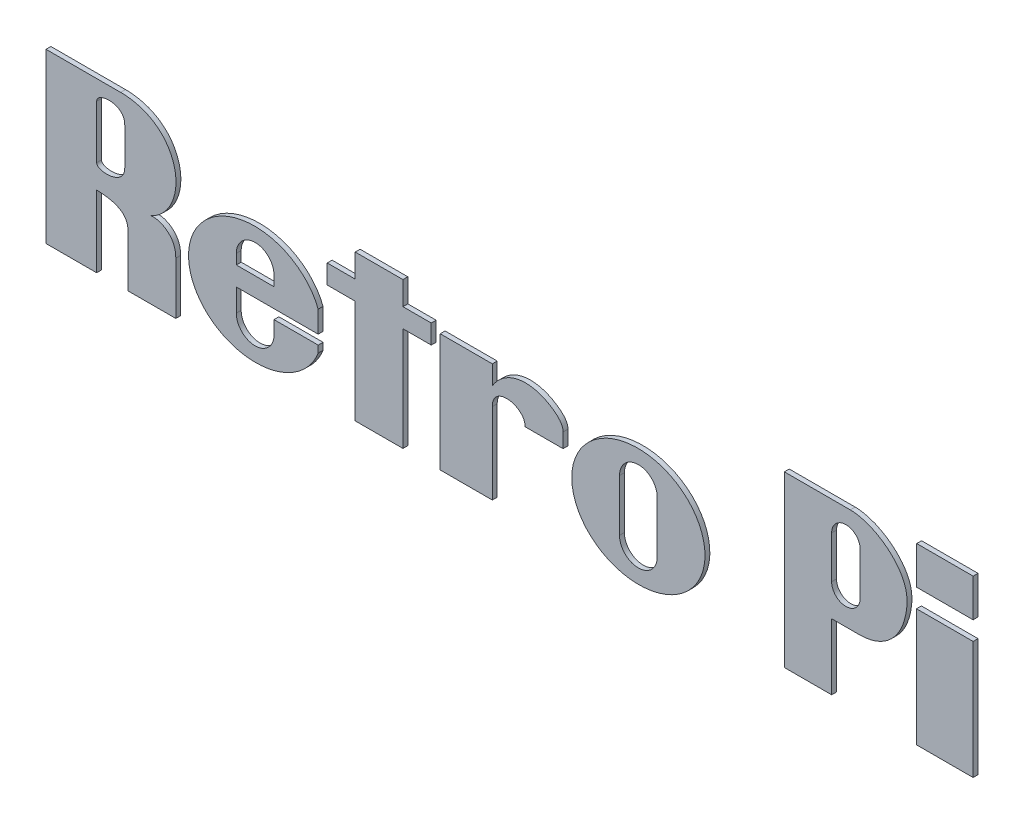
SolidWorks part; units mm, degrees
ref_plane "Front Plane" through (0, 0, 0) normal (0, 0, 1) x (1, 0, 0)
ref_plane "Top Plane" through (0, 0, 0) normal (0, 1, 0) x (1, 0, 0)
ref_plane "Right Plane" through (0, 0, 0) normal (1, 0, 0) x (0, 0, -1)
sketch "Sketch1" plane through (0, 0, 0) normal (0, 0, 1) x (1, 0, 0)
  line L0 (7.695, 27.3237) -> (140.3617, 27.3237) construction
  line L1 (-30.2633, -2.8229) -> (-30.2633, -4.6928)
  line L2 (-30.2633, -4.6928) -> (-31.5821, -4.6928)
  line L3 (-31.5821, -4.6928) -> (-31.5821, -0.3107)
  line L4 (-31.5821, -0.3107) -> (-29.6366, -0.3107)
  line L5 (-30.2633, -2.2096) -> (-30.2633, -0.8264)
  line L6 (-28.2011, -3.3328) -> (-28.2011, -4.6928)
  line L7 (-28.2011, -4.6928) -> (-29.4478, -4.6928)
  line L8 (-29.4478, -4.6928) -> (-29.4478, -3.3328)
  line L9 (-26.134, -2.4358) -> (-26.134, -3.7851) construction
  line L10 (-25.6426, -2.4358) -> (-25.6426, -2.6977)
  line L11 (-26.6254, -2.4358) -> (-26.6254, -2.6977)
  line L12 (-23.5277, -1.9664) -> (-23.5277, -4.6667)
  line L13 (-24.2562, -1.4682) -> (-23.5277, -1.4682)
  line L14 (-24.2562, -1.4682) -> (-24.2562, -1.9664)
  line L15 (-24.2562, -1.9664) -> (-23.5277, -1.9664)
  line L16 (-21.5475, -1.4682) -> (-21.5475, -1.9664)
  line L17 (-23.5277, -0.8569) -> (-22.2843, -0.8569)
  line L18 (-23.5277, -0.8569) -> (-23.5277, -1.4682)
  line L19 (-23.5277, -4.6667) -> (-22.2843, -4.6667)
  line L20 (-22.2843, -0.8569) -> (-22.2843, -1.4682)
  line L21 (-22.2843, -1.4682) -> (-21.5475, -1.4682)
  line L22 (-22.2843, -1.9664) -> (-22.2843, -4.6667)
  line L23 (-22.2843, -1.9664) -> (-21.5475, -1.9664)
  line L24 (-29.5308, -0.988) -> (-29.5308, -1.9664)
  line L25 (-21.313, -1.5938) -> (-19.9566, -1.5938)
  line L26 (-21.313, -1.5938) -> (-21.313, -4.6667)
  line L27 (-21.313, -4.6667) -> (-19.9566, -4.6667)
  line L28 (-19.9566, -1.5938) -> (-19.9566, -2.0894)
  line L29 (-12.3495, -0.2259) -> (-10.6322, -0.2259)
  line L30 (-12.3495, -0.2259) -> (-12.3495, -4.6407)
  line L31 (-12.3495, -4.6407) -> (-11.1172, -4.6407)
  line L32 (-11.1172, -4.6407) -> (-11.1172, -2.9238)
  line L33 (-8.9022, -0.1203) -> (-7.4323, -0.1203)
  line L34 (-8.9022, -0.1203) -> (-8.9022, -1.1066)
  line L35 (-8.9022, -1.1066) -> (-7.4323, -1.1066)
  line L36 (-7.4323, -0.1203) -> (-7.4323, -1.1066)
  line L37 (-8.907, -1.5938) -> (-7.4323, -1.5938)
  line L38 (-8.907, -1.5938) -> (-8.907, -4.664)
  line L39 (-8.907, -4.664) -> (-7.4323, -4.664)
  line L40 (-7.4323, -1.5938) -> (-7.4323, -4.664)
  line L41 (-24.4919, -2.6294) -> (-24.4919, -3.1934)
  line L42 (-17.6786, -2.3552) -> (-17.6786, -2.5863) construction
  line L43 (-24.4919, -3.4389) -> (-25.6426, -3.4389)
  line L44 (-24.4919, -3.1934) -> (-26.6254, -3.1934)
  line L45 (-19.1018, -2.5863) -> (-18.1131, -2.5863)
  line L46 (-18.1131, -2.5863) -> (-18.1131, -2.2096)
  line L47 (-19.9566, -2.5595) -> (-19.9566, -4.6667)
  line L48 (-16.1521, -2.4557) -> (-16.1521, -3.805) construction
  line L49 (-15.6608, -2.4557) -> (-15.6608, -3.805)
  line L50 (-16.6435, -2.4557) -> (-16.6435, -3.805)
  line L51 (-26.6254, -2.6977) -> (-25.6426, -2.6977)
  line L52 (-24.4919, -3.4389) -> (-24.4919, -3.6194)
  line L53 (-25.6426, -3.4389) -> (-25.6426, -3.7851)
  line L54 (-26.6254, -3.1934) -> (-26.6254, -3.7851)
  line L55 (-10.7458, -0.988) -> (-10.7458, -2.0894) construction
  line L56 (-10.3735, -0.988) -> (-10.3735, -2.0894)
  line L57 (-11.118, -0.988) -> (-11.118, -2.0894)
  line L58 (-11.1172, -2.9238) -> (-10.3913, -2.9238)
  arc A0 (-15.6608, -2.4557) -> (-16.6435, -2.4557) centre (-16.1521, -2.4557) ccw
  arc A1 (-16.6435, -3.805) -> (-15.6608, -3.805) centre (-16.1521, -3.805) ccw
  arc A2 (-25.6426, -2.4358) -> (-26.6254, -2.4358) centre (-26.134, -2.4358) ccw
  arc A3 (-26.6254, -3.7851) -> (-25.6426, -3.7851) centre (-26.134, -3.7851) ccw
  arc A4 (-10.3735, -0.988) -> (-11.118, -0.988) centre (-10.7458, -0.988) ccw
  arc A5 (-11.118, -2.0894) -> (-10.3735, -2.0894) centre (-10.7458, -2.0894) ccw
  ellipse E0 centre (-16.1521, -3.1341) end of major axis (-17.8866, -3.0849) minor radius 1.5332
  ellipse E1 centre (-26.134, -3.1142) end of major axis (-24.3995, -3.1634) minor radius 1.5332 (-24.4919, -2.6294) -> (-24.4919, -3.6194) ccw
  spline S0 degree 3 poles (-29.6366, -0.3107) (-29.1367, -0.3107) (-28.4721, -0.6107) (-28.0426, -1.7411) (-28.4049, -2.5033) (-28.8544, -2.6977) knots 0 0 0 0 0.382534 0.585861 1 1 1 1
  spline S1 degree 3 poles (-28.8544, -2.6977) (-28.6401, -2.6707) (-28.2847, -2.8632) (-28.2011, -3.1887) (-28.2011, -3.3328) knots 0 0 0 0 0.61778 1 1 1 1
  spline S2 degree 3 poles (-30.2633, -2.8229) (-29.648, -2.8443) (-29.4478, -3.04) (-29.4478, -3.3328) knots 0 0 0 0 1 1 1 1
  spline S3 degree 3 poles (-30.2633, -0.8264) (-30.2633, -0.5805) (-29.5308, -0.5238) (-29.5308, -0.988) knots 0 0 0 0 1 1 1 1
  spline S4 degree 3 poles (-30.2633, -2.2096) (-30.2633, -2.4029) (-29.5308, -2.4124) (-29.5308, -1.9664) knots 0 0 0 0 1 1 1 1
  spline S5 degree 3 poles (-10.6322, -0.2259) (-10.0341, -0.2259) (-9.0833, -0.8806) (-9.2252, -2.5118) (-9.8323, -2.9238) (-10.3913, -2.9238) knots 0 0 0 0 0.403061 0.503061 1 1 1 1
  spline S8 degree 3 poles (-19.9566, -2.0894) (-19.5799, -1.4836) (-18.698, -1.4592) (-18.1131, -2.0554) (-18.1131, -2.2096) knots 0 0 0 0 0.802412 1 1 1 1
  spline S9 degree 3 poles (-19.9566, -2.5595) (-19.9566, -1.9923) (-19.0995, -2.1358) (-19.1018, -2.5863) knots 0 0 0 0 1 1 1 1
  point P58 (-26.134, -3.1105)
  point P84 (-16.1521, -3.1304)
  point P102 (-10.7458, -1.5387)
extrude "Boss-Extrude1" add sketch "Sketch1" along normal blind 0.127
